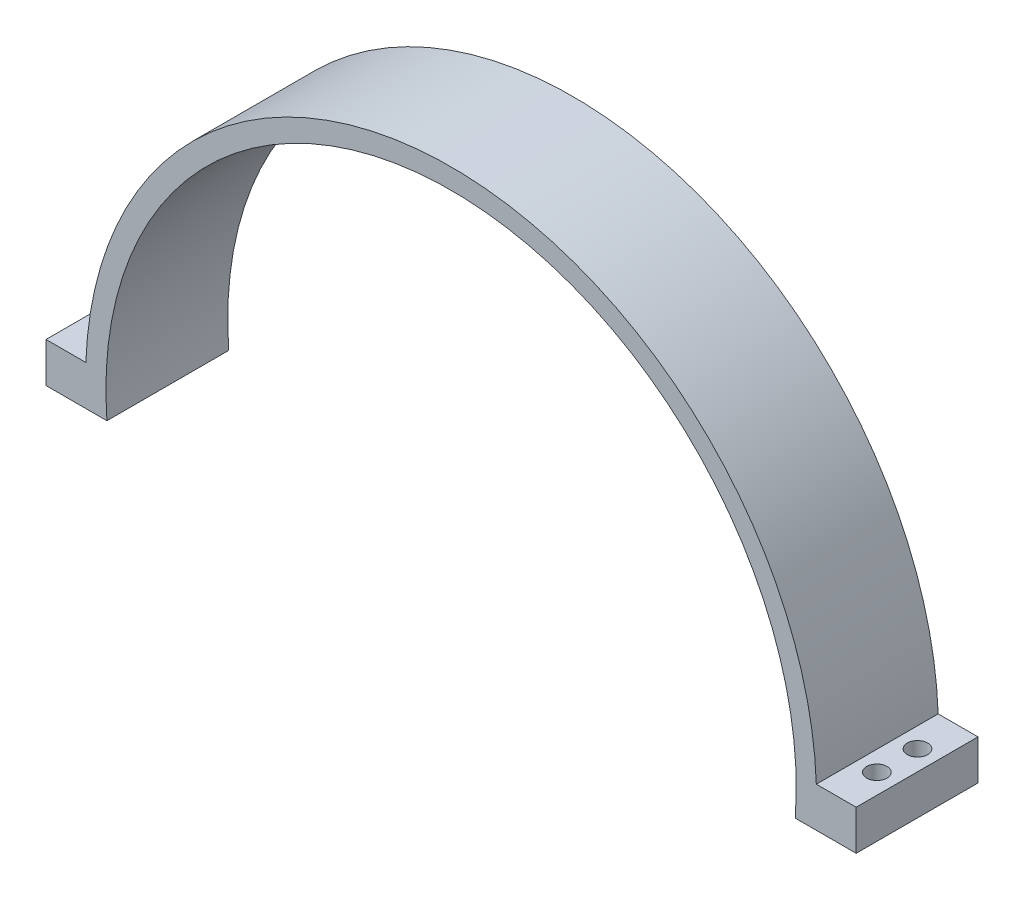
SolidWorks part; units mm, degrees
ref_plane "Ön Düzlem" through (0, 0, 0) normal (0, 0, 1) x (1, 0, 0)
ref_plane "Üst Düzlem" through (0, 0, 0) normal (0, 1, 0) x (1, 0, 0)
ref_plane "Sağ Düzlem" through (0, 0, 0) normal (1, 0, 0) x (0, 0, -1)
sketch "Sketch1" plane through (0, 0, 0) normal (0, 0, 1) x (1, 0, 0)
  line L0 (0, 85) -> (0, 0) construction
  line L5 (89.9391, 3.3095) -> (99.7492, 3.3095)
  line L6 (99.7492, 3.3095) -> (99.7492, -6.5253)
  line L7 (99.7492, -6.5253) -> (84.7492, -6.5253)
  line L9 (-89.9391, 3.3095) -> (-99.7492, 3.3095)
  line L10 (-99.7492, 3.3095) -> (-99.7492, -6.5253)
  line L11 (-99.7492, -6.5253) -> (-84.7492, -6.5253)
  arc A2 (84.7492, -6.5253) -> (-84.7492, -6.5253) centre (0, 0) ccw
  arc A4 (89.9391, 3.3095) -> (-89.9391, 3.3095) centre (0, 0) ccw
  dimension "D1" = 15
  dimension "D2" = 85
  dimension "D3" = 90
extrude "Boss-Extrude1" add sketch "Sketch1" along normal blind 30
sketch "Sketch2" plane through (0, 3.3095, 0) normal (0, 1, 0) x (1, 0, 0)
  line L0 (0, 0) -> (0, -30) construction
  line L1 (89.9391, 0) -> (-89.9391, 0) construction
  line L2 (-89.9391, -30) -> (89.9391, -30) construction
  line L3 (-94.8441, 0) -> (-94.8441, -30) construction
  line L4 (-89.9391, 0) -> (-99.7492, 0) construction
  line L5 (-89.9391, -30) -> (-99.7492, -30) construction
  circle A0 centre (-94.8441, -10) radius 2.5
  circle A1 centre (-94.8441, -20) radius 2.5
  circle A2 centre (94.8441, -20) radius 2.5
  circle A3 centre (94.8441, -10) radius 2.5
  dimension "D2" = 5
  dimension "D3" = 5
  dimension "D1" = 10
  dimension "D4" = 10
extrude "Cut-Extrude1" cut sketch "Sketch2" against normal blind 30
